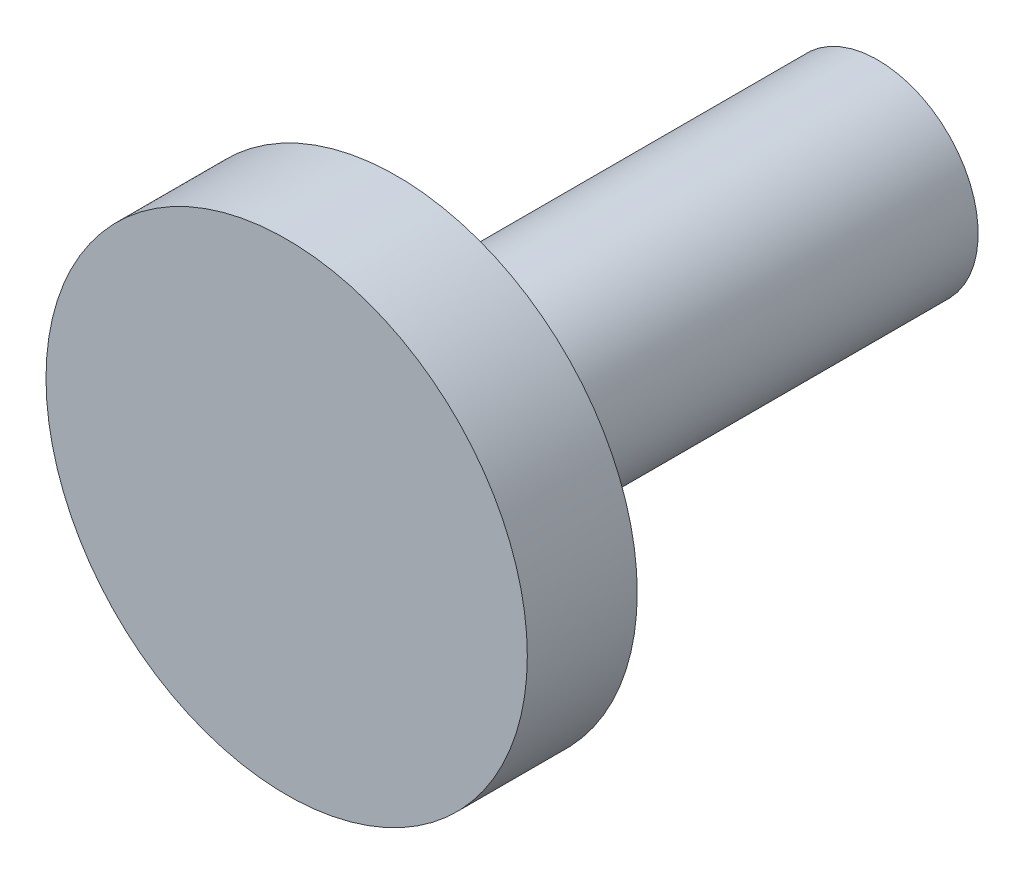
SolidWorks part; units mm, degrees
ref_plane "Plan de face" through (0, 0, 0) normal (0, 0, 1) x (1, 0, 0)
ref_plane "Plan de dessus" through (0, 0, 0) normal (0, 1, 0) x (1, 0, 0)
ref_plane "Plan de droite" through (0, 0, 0) normal (1, 0, 0) x (0, 0, -1)
sketch "Esquisse1" plane through (0, 0, 0) normal (0, 0, 1) x (1, 0, 0)
  circle A0 centre (0, 0) radius 3
  dimension "D1" = 6
extrude "Boss.-Extru.1" add sketch "Esquisse1" along normal blind 1.37
sketch "Esquisse2" plane through (0, 0, 0) normal (0, 0, -1) x (-1, 0, 0)
  circle A0 centre (0, 0) radius 1.25
  dimension "D1" = 2.5
extrude "Boss.-Extru.2" add sketch "Esquisse2" along normal blind 6
